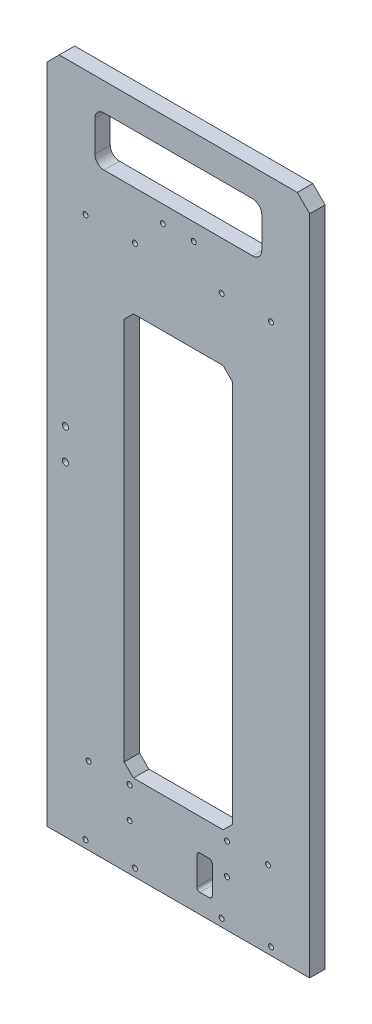
SolidWorks part; units mm, degrees
ref_plane "Front" through (0, 0, 0) normal (0, 0, 1) x (1, 0, 0)
ref_plane "Top" through (0, 0, 0) normal (0, 1, 0) x (1, 0, 0)
ref_plane "Right" through (0, 0, 0) normal (1, 0, 0) x (0, 0, -1)
sketch "Model" plane through (0, 0, 0) normal (0, 0, 1) x (1, 0, 0)
  line L0 (85, 428) -> (85, 0)
  line L1 (85, 428) -> (77, 436)
  line L2 (85, 0) -> (-85, 0)
  line L3 (-77, 436) -> (77, 436)
  line L4 (-85, 0) -> (-85, 428)
  line L5 (-85, 428) -> (-77, 436)
  line L6 (14, 34.5) -> (20, 34.5)
  line L7 (12, 14.5) -> (12, 32.5)
  line L8 (22, 32.5) -> (22, 14.5)
  line L9 (20, 12.5) -> (14, 12.5)
  line L10 (-29, 315) -> (29, 315)
  line L11 (-29, 315) -> (-35, 309)
  line L12 (29, 315) -> (35, 309)
  line L13 (-35, 61) -> (-35, 309)
  line L14 (35, 309) -> (35, 61)
  line L15 (-29, 55) -> (-35, 61)
  line L16 (35, 61) -> (29, 55)
  line L17 (29, 55) -> (-29, 55)
  line L18 (-54, 392) -> (-54, 412)
  line L19 (48, 386) -> (-48, 386)
  line L20 (54, 412) -> (54, 392)
  line L21 (-48, 418) -> (48, 418)
  circle A0 centre (-31.5, 50) radius 1.6
  circle A1 centre (-31.5, 30) radius 1.6
  circle A2 centre (31.5, 30) radius 1.6
  circle A3 centre (31.5, 50) radius 1.6
  arc A4 (14, 34.5) -> (12, 32.5) centre (14, 32.5) ccw
  arc A5 (22, 32.5) -> (20, 34.5) centre (20, 32.5) ccw
  arc A6 (12, 14.5) -> (14, 12.5) centre (14, 14.5) ccw
  arc A7 (20, 12.5) -> (22, 14.5) centre (20, 14.5) ccw
  circle A8 centre (-58, 50) radius 1.6
  circle A9 centre (-73, 210) radius 2
  circle A10 centre (-73, 230) radius 2
  circle A11 centre (60, 355) radius 1.6
  circle A12 centre (58, 50) radius 1.6
  circle A13 centre (-60, 355) radius 1.6
  circle A14 centre (-28, 355) radius 1.6
  circle A15 centre (28, 355) radius 1.6
  circle A16 centre (60, 5) radius 1.6
  circle A17 centre (28, 5) radius 1.6
  circle A18 centre (-28, 5) radius 1.6
  circle A19 centre (-60, 5) radius 1.6
  circle A20 centre (10, 375) radius 1.6
  circle A21 centre (-10, 375) radius 1.6
  arc A22 (-48, 418) -> (-54, 412) centre (-48, 412) ccw
  arc A23 (-54, 392) -> (-48, 386) centre (-48, 392) ccw
  arc A24 (48, 386) -> (54, 392) centre (48, 392) ccw
  arc A25 (54, 412) -> (48, 418) centre (48, 412) ccw
extrude "Boss-Extrude1" add sketch "Model" along normal blind 10
